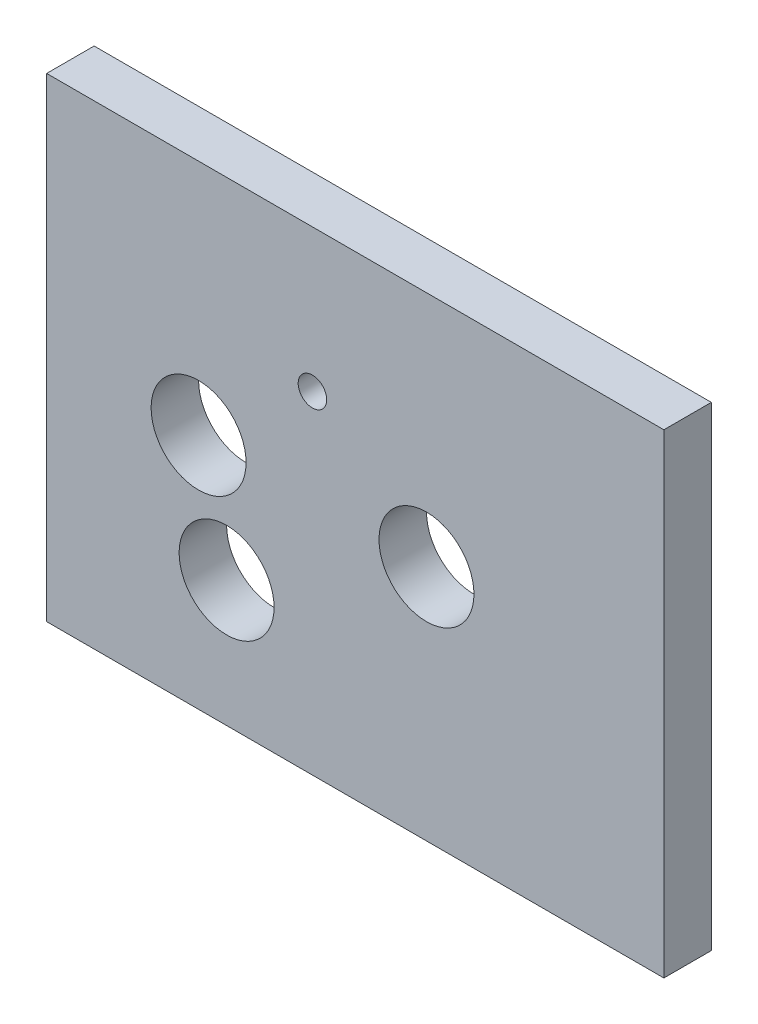
SolidWorks part; units mm, degrees
ref_plane "Front Plane" through (0, 0, 0) normal (0, 0, 1) x (1, 0, 0)
ref_plane "Top Plane" through (0, 0, 0) normal (0, 1, 0) x (1, 0, 0)
ref_plane "Right Plane" through (0, 0, 0) normal (1, 0, 0) x (0, 0, -1)
sketch "Sketch3" plane through (0, 0, 0) normal (0, 0, 1) x (1, 0, 0)
  line L1 (0, 0) -> (65, 0)
  line L2 (0, 0) -> (0, -50)
  line L3 (0, -50) -> (65, -50)
  line L4 (65, 0) -> (65, -50)
  dimension "D1" = 65
  dimension "D2" = 50
extrude "Boss-Extrude2" add sketch "Sketch3" along normal blind 5
sketch "Sketch4" plane through (0, 0, 5) normal (0, 0, 1) x (1, 0, 0)
  line L0 (65, -50) -> (65, 0) construction
  circle A0 centre (40, -25) radius 1.5
  circle A1 centre (16, -25) radius 1.5
  circle A2 centre (27.987, -15.0164) radius 1.5
  dimension "D2" = 3
  dimension "D3" = 3
  dimension "D5" = 3
  dimension "D1" = 25
  dimension "D4" = 24
  dimension "D6" = 15.6
  dimension "D7" = 15.62
extrude "Cut-Extrude2" cut sketch "Sketch4" against normal blind 5
sketch "Sketch5" plane through (0, 0, 0) normal (0, 0, -1) x (-1, 0, 0)
  line L0 (-40, -25) -> (-16, -25)
  line L1 (-16, -25) -> (-18.95, -36.7349)
  line L2 (-18.95, -36.7349) -> (-40, -25)
  circle A0 centre (-18.95, -36.7349) radius 5
  circle A1 centre (-40, -25) radius 5
  circle A2 centre (-16, -25) radius 5
  circle M2 centre (-16, -25) radius 1.5
  circle M4 centre (-40, -25) radius 1.5
  dimension "D3" = 10
  dimension "D4" = 10
  dimension "D5" = 10
  dimension "D1" = 24.1
  dimension "D2" = 12.1
extrude "Cut-Extrude3" cut sketch "Sketch5" against normal blind 10 contours L0 A1 L2 M4 | L2 A0 L1 | L1 A0 L2 | L0 A2 L1 M2 | L1 A2 L0 M2 | L2 A1 L0 M4
